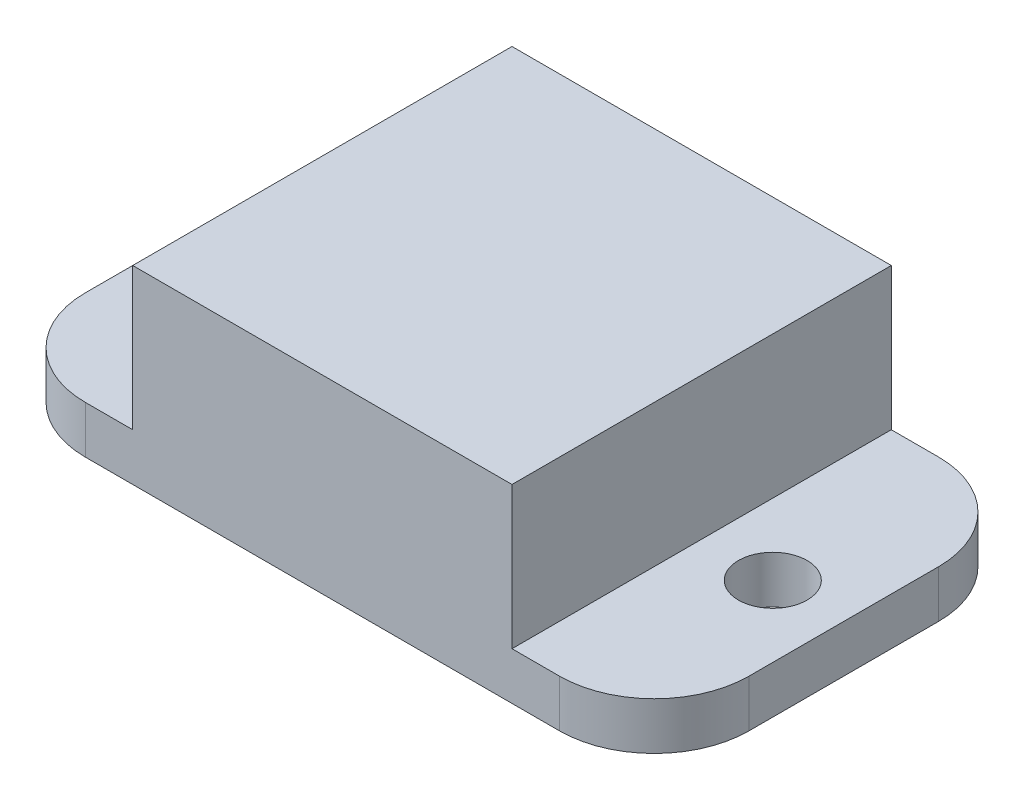
SolidWorks part; units mm, degrees
ref_plane "Front Plane" through (0, 0, 0) normal (0, 0, 1) x (1, 0, 0)
ref_plane "Top Plane" through (0, 0, 0) normal (0, 1, 0) x (1, 0, 0)
ref_plane "Right Plane" through (0, 0, 0) normal (1, 0, 0) x (0, 0, -1)
sketch "Sketch1" plane through (0, 0, 0) normal (0, 0, 1) x (1, 0, 0)
  line L0 (0, 0) -> (0, 3.175)
  line L1 (0, 3.175) -> (9.525, 3.175)
  line L2 (9.525, 3.175) -> (9.525, 12.7)
  line L3 (9.525, 12.7) -> (34.925, 12.7)
  line L4 (34.925, 12.7) -> (34.925, 3.175)
  line L5 (34.925, 3.175) -> (44.45, 3.175)
  line L6 (44.45, 3.175) -> (44.45, 0)
  line L7 (44.45, 0) -> (0, 0)
  point P9 (44.45, 1.5875)
  point P10 (22.225, 12.7)
  point P11 (22.225, 0)
  point P12 (0, 0)
  dimension "D1" = 44.45
  dimension "D2" = 25.4
  dimension "D3" = 12.7
  dimension "D4" = 3.175
extrude "Boss-Extrude1" add sketch "Sketch1" along normal blind 25.4
sketch "Sketch2" plane through (0, 3.175, 0) normal (0, 1, 0) x (1, 0, 0)
  line L0 (4.7625, -12.7) -> (39.6875, -12.7) construction
  line L1 (34.925, 0) -> (9.525, 0) construction
  line L2 (0, -25.4) -> (0, 0) construction
  circle A0 centre (4.7625, -12.7) radius 2.3
  circle A1 centre (39.6875, -12.7) radius 2.3
  point P4 (22.225, 0)
  point P5 (0, 0)
  point P8 (22.225, -12.7)
  point P9 (0, 0)
  point P10 (0, -12.7)
  dimension "D1" = 4.6
  dimension "D2" = 4.6
  dimension "D3" = 34.925
extrude "Cut-Extrude1" cut sketch "Sketch2" against normal through all both
fillet "Fillet1" radius 6.35 4 edges at (0, 1.5875, 0) (0, 1.5875, 25.4) (44.45, 1.5875, 0) (44.45, 1.5875, 25.4)
